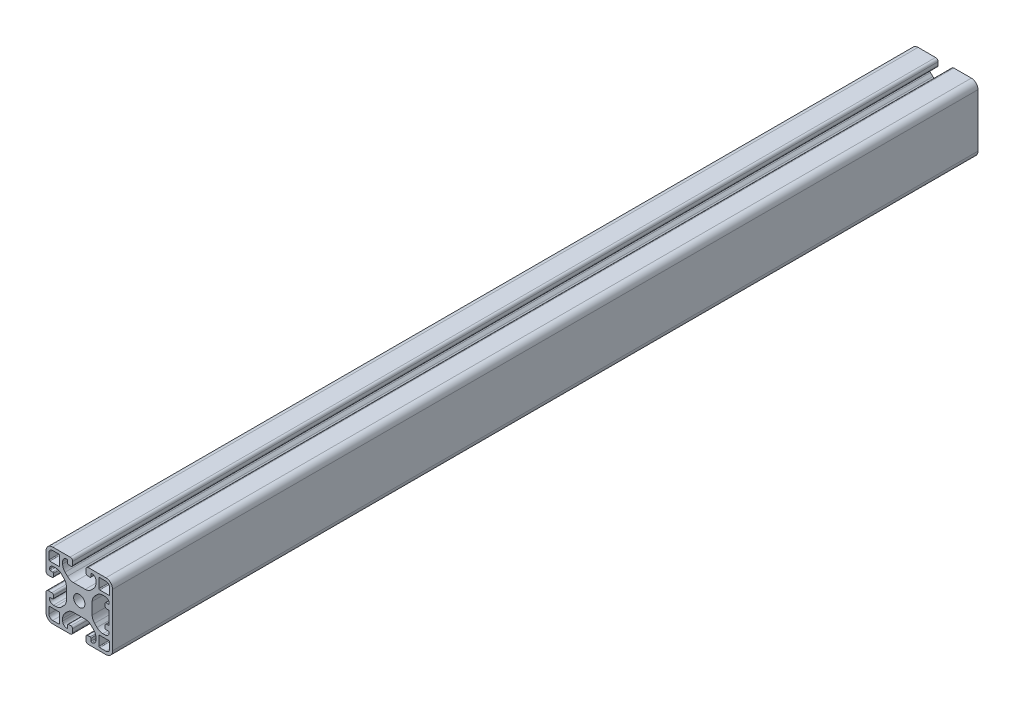
SolidWorks part; units mm, degrees
ref_plane "Piano frontale" through (0, 0, 0) normal (0, 0, 1) x (1, 0, 0)
ref_plane "Piano superiore" through (0, 0, 0) normal (0, 1, 0) x (1, 0, 0)
ref_plane "Piano destro" through (0, 0, 0) normal (1, 0, 0) x (0, 0, -1)
ref_plane "Piano1" through (0, 0, -340) normal (0, 0, -1) x (-1, 0, 0)
sketch "Schizzo1" plane through (0, 0, -340) normal (0, 0, -1) x (-1, 0, 0)
  line L0 (-12.3, -18.2) -> (-16, -18.2)
  line L1 (-18.2, -16) -> (-18.2, -12.3)
  line L2 (-17.7, -11.8) -> (-12.3, -11.8)
  line L3 (-11.8, -12.3) -> (-11.8, -17.7)
  line L4 (-11.8, 17.7) -> (-11.8, 12.3)
  line L5 (-12.3, 11.8) -> (-17.7, 11.8)
  line L6 (-18.2, 12.3) -> (-18.2, 16)
  line L7 (-16, 18.2) -> (-12.3, 18.2)
  line L8 (18.2, 16) -> (18.2, 12.3)
  line L9 (17.7, 11.8) -> (12.3, 11.8)
  line L10 (11.8, 12.3) -> (11.8, 17.7)
  line L11 (12.3, 18.2) -> (16, 18.2)
  line L12 (6.5, -15.5) -> (5, -15.5)
  line L13 (4, -16.5) -> (4, -18.5)
  line L14 (5.5, -20) -> (16, -20)
  line L15 (20, -16) -> (20, -5.5)
  line L16 (18.5, -4) -> (16.5, -4)
  line L17 (15.5, -5) -> (15.5, -6.5)
  line L18 (16, -7) -> (17.55, -7)
  line L19 (18, -7.45) -> (18, -7.5)
  line L20 (15.5, -10) -> (14.1924, -10)
  line L21 (10.6569, -8.5355) -> (9.2145, -7.0931)
  line L22 (7.75, -3.5576) -> (7.75, 3.5576)
  line L23 (9.2145, 7.0931) -> (10.6569, 8.5355)
  line L24 (14.1924, 10) -> (15.5, 10)
  line L25 (18, 7.5) -> (18, 7.45)
  line L26 (17.55, 7) -> (16, 7)
  line L27 (15.5, 6.5) -> (15.5, 5)
  line L28 (16.5, 4) -> (18.5, 4)
  line L29 (20, 5.5) -> (20, 16)
  line L30 (16, 20) -> (5.5, 20)
  line L31 (4, 18.5) -> (4, 16.5)
  line L32 (5, 15.5) -> (6.5, 15.5)
  line L33 (7, 16) -> (7, 17.55)
  line L34 (7.45, 18) -> (7.5, 18)
  line L35 (10, 15.5) -> (10, 14.1924)
  line L36 (8.5355, 10.6569) -> (7.0931, 9.2145)
  line L37 (3.5576, 7.75) -> (-3.5576, 7.75)
  line L38 (-7.0931, 9.2145) -> (-8.5355, 10.6569)
  line L39 (-10, 14.1924) -> (-10, 15.5)
  line L40 (-7.5, 18) -> (-7.45, 18)
  line L41 (-7, 17.55) -> (-7, 16)
  line L42 (-6.5, 15.5) -> (-5, 15.5)
  line L43 (-4, 16.5) -> (-4, 18.5)
  line L44 (-5.5, 20) -> (-16, 20)
  line L45 (-20, 16) -> (-20, -16)
  line L46 (-16, -20) -> (-5.5, -20)
  line L47 (-4, -18.5) -> (-4, -16.5)
  line L48 (-5, -15.5) -> (-6.5, -15.5)
  line L49 (-7, -16) -> (-7, -17.55)
  line L50 (-7.45, -18) -> (-7.5, -18)
  line L51 (-10, -15.5) -> (-10, -14.1924)
  line L52 (-8.5355, -10.6569) -> (-7.0931, -9.2145)
  line L53 (-3.5576, -7.75) -> (3.5576, -7.75)
  line L54 (7.0931, -9.2145) -> (8.5355, -10.6569)
  line L55 (10, -14.1924) -> (10, -15.5)
  line L56 (7.5, -18) -> (7.45, -18)
  line L57 (7, -17.55) -> (7, -16)
  line L58 (18.2, -12.3) -> (18.2, -16)
  line L59 (16, -18.2) -> (12.3, -18.2)
  line L60 (11.8, -17.7) -> (11.8, -12.3)
  line L61 (12.3, -11.8) -> (17.7, -11.8)
  line L62 (-16, 7) -> (-17.5, 7)
  line L63 (-15.5, 10) -> (-14.1924, 10)
  line L64 (-10.6569, 8.5355) -> (-9.2145, 7.0931)
  line L65 (-7.75, 3.5576) -> (-7.75, -3.5576)
  line L66 (-9.2145, -7.0931) -> (-10.6569, -8.5355)
  line L67 (-14.1924, -10) -> (-15.5, -10)
  line L68 (-17.5, -7) -> (-16, -7)
  line L69 (-15.5, -6.5) -> (-15.5, -5)
  line L70 (-16.5, -4) -> (-17.5, -4)
  line L71 (-18, -3.5) -> (-18, 3.5)
  line L72 (-17.5, 4) -> (-16.5, 4)
  line L73 (-15.5, 5) -> (-15.5, 6.5)
  arc A0 (-16, -18.2) -> (-18.2, -16) centre (-16, -16) cw
  arc A1 (-18.2, -12.3) -> (-17.7, -11.8) centre (-17.7, -12.3) cw
  arc A2 (-12.3, -11.8) -> (-11.8, -12.3) centre (-12.3, -12.3) cw
  arc A3 (-11.8, -17.7) -> (-12.3, -18.2) centre (-12.3, -17.7) cw
  arc A4 (-12.3, 18.2) -> (-11.8, 17.7) centre (-12.3, 17.7) cw
  arc A5 (-11.8, 12.3) -> (-12.3, 11.8) centre (-12.3, 12.3) cw
  arc A6 (-17.7, 11.8) -> (-18.2, 12.3) centre (-17.7, 12.3) cw
  arc A7 (-18.2, 16) -> (-16, 18.2) centre (-16, 16) cw
  arc A8 (16, 18.2) -> (18.2, 16) centre (16, 16) cw
  arc A9 (18.2, 12.3) -> (17.7, 11.8) centre (17.7, 12.3) cw
  arc A10 (12.3, 11.8) -> (11.8, 12.3) centre (12.3, 12.3) cw
  arc A11 (11.8, 17.7) -> (12.3, 18.2) centre (12.3, 17.7) cw
  arc A12 (5, -15.5) -> (4, -16.5) centre (5, -16.5) ccw
  arc A13 (4, -18.5) -> (5.5, -20) centre (5.5, -18.5) ccw
  arc A14 (16, -20) -> (20, -16) centre (16, -16) ccw
  arc A15 (20, -5.5) -> (18.5, -4) centre (18.5, -5.5) ccw
  arc A16 (16.5, -4) -> (15.5, -5) centre (16.5, -5) ccw
  arc A17 (15.5, -6.5) -> (16, -7) centre (16, -6.5) ccw
  arc A18 (17.55, -7) -> (18, -7.45) centre (17.55, -7.45) cw
  arc A19 (18, -7.5) -> (15.5, -10) centre (15.5, -7.5) cw
  arc A20 (14.1924, -10) -> (10.6569, -8.5355) centre (14.1924, -5) cw
  arc A21 (9.2145, -7.0931) -> (7.75, -3.5576) centre (12.75, -3.5576) cw
  arc A22 (7.75, 3.5576) -> (9.2145, 7.0931) centre (12.75, 3.5576) cw
  arc A23 (10.6569, 8.5355) -> (14.1924, 10) centre (14.1924, 5) cw
  arc A24 (15.5, 10) -> (18, 7.5) centre (15.5, 7.5) cw
  arc A25 (18, 7.45) -> (17.55, 7) centre (17.55, 7.45) cw
  arc A26 (16, 7) -> (15.5, 6.5) centre (16, 6.5) ccw
  arc A27 (15.5, 5) -> (16.5, 4) centre (16.5, 5) ccw
  arc A28 (18.5, 4) -> (20, 5.5) centre (18.5, 5.5) ccw
  arc A29 (20, 16) -> (16, 20) centre (16, 16) ccw
  arc A30 (5.5, 20) -> (4, 18.5) centre (5.5, 18.5) ccw
  arc A31 (4, 16.5) -> (5, 15.5) centre (5, 16.5) ccw
  arc A32 (6.5, 15.5) -> (7, 16) centre (6.5, 16) ccw
  arc A33 (7, 17.55) -> (7.45, 18) centre (7.45, 17.55) cw
  arc A34 (7.5, 18) -> (10, 15.5) centre (7.5, 15.5) cw
  arc A35 (10, 14.1924) -> (8.5355, 10.6569) centre (5, 14.1924) cw
  arc A36 (7.0931, 9.2145) -> (3.5576, 7.75) centre (3.5576, 12.75) cw
  arc A37 (-3.5576, 7.75) -> (-7.0931, 9.2145) centre (-3.5576, 12.75) cw
  arc A38 (-8.5355, 10.6569) -> (-10, 14.1924) centre (-5, 14.1924) cw
  arc A39 (-10, 15.5) -> (-7.5, 18) centre (-7.5, 15.5) cw
  arc A40 (-7.45, 18) -> (-7, 17.55) centre (-7.45, 17.55) cw
  arc A41 (-7, 16) -> (-6.5, 15.5) centre (-6.5, 16) ccw
  arc A42 (-5, 15.5) -> (-4, 16.5) centre (-5, 16.5) ccw
  arc A43 (-4, 18.5) -> (-5.5, 20) centre (-5.5, 18.5) ccw
  arc A44 (-16, 20) -> (-20, 16) centre (-16, 16) ccw
  arc A45 (-20, -16) -> (-16, -20) centre (-16, -16) ccw
  arc A46 (-5.5, -20) -> (-4, -18.5) centre (-5.5, -18.5) ccw
  arc A47 (-4, -16.5) -> (-5, -15.5) centre (-5, -16.5) ccw
  arc A48 (-6.5, -15.5) -> (-7, -16) centre (-6.5, -16) ccw
  arc A49 (-7, -17.55) -> (-7.45, -18) centre (-7.45, -17.55) cw
  arc A50 (-7.5, -18) -> (-10, -15.5) centre (-7.5, -15.5) cw
  arc A51 (-10, -14.1924) -> (-8.5355, -10.6569) centre (-5, -14.1924) cw
  arc A52 (-7.0931, -9.2145) -> (-3.5576, -7.75) centre (-3.5576, -12.75) cw
  arc A53 (3.5576, -7.75) -> (7.0931, -9.2145) centre (3.5576, -12.75) cw
  arc A54 (8.5355, -10.6569) -> (10, -14.1924) centre (5, -14.1924) cw
  arc A55 (10, -15.5) -> (7.5, -18) centre (7.5, -15.5) cw
  arc A56 (7.45, -18) -> (7, -17.55) centre (7.45, -17.55) cw
  arc A57 (7, -16) -> (6.5, -15.5) centre (6.5, -16) ccw
  arc A58 (17.7, -11.8) -> (18.2, -12.3) centre (17.7, -12.3) cw
  arc A59 (18.2, -16) -> (16, -18.2) centre (16, -16) cw
  arc A60 (12.3, -18.2) -> (11.8, -17.7) centre (12.3, -17.7) cw
  arc A61 (11.8, -12.3) -> (12.3, -11.8) centre (12.3, -12.3) cw
  circle A62 centre (0, 0) radius 3.4
  arc A63 (-15.5, 6.5) -> (-16, 7) centre (-16, 6.5) ccw
  arc A64 (-17.5, 7) -> (-18, 7.5) centre (-17.5, 7.5) cw
  arc A65 (-18, 7.5) -> (-15.5, 10) centre (-15.5, 7.5) cw
  arc A66 (-14.1924, 10) -> (-10.6569, 8.5355) centre (-14.1924, 5) cw
  arc A67 (-9.2145, 7.0931) -> (-7.75, 3.5576) centre (-12.75, 3.5576) cw
  arc A68 (-7.75, -3.5576) -> (-9.2145, -7.0931) centre (-12.75, -3.5576) cw
  arc A69 (-10.6569, -8.5355) -> (-14.1924, -10) centre (-14.1924, -5) cw
  arc A70 (-15.5, -10) -> (-18, -7.5) centre (-15.5, -7.5) cw
  arc A71 (-18, -7.5) -> (-17.5, -7) centre (-17.5, -7.5) cw
  arc A72 (-16, -7) -> (-15.5, -6.5) centre (-16, -6.5) ccw
  arc A73 (-15.5, -5) -> (-16.5, -4) centre (-16.5, -5) ccw
  arc A74 (-17.5, -4) -> (-18, -3.5) centre (-17.5, -3.5) cw
  arc A75 (-18, 3.5) -> (-17.5, 4) centre (-17.5, 3.5) cw
  arc A76 (-16.5, 4) -> (-15.5, 5) centre (-16.5, 5) ccw
extrude "Estrusione-Estrusione1" add sketch "Schizzo1" against normal blind 520
